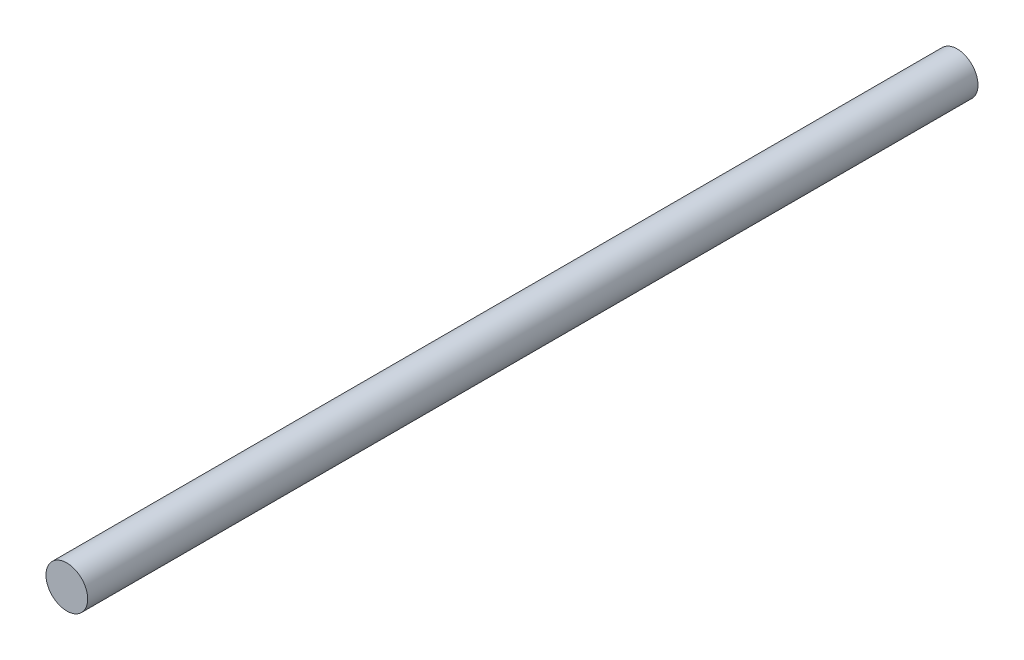
SolidWorks part; units mm, degrees
material "PE High Density"
ref_plane "Front Plane" through (0, 0, 0) normal (0, 0, 1) x (1, 0, 0)
ref_plane "Top Plane" through (0, 0, 0) normal (0, 1, 0) x (1, 0, 0)
ref_plane "Right Plane" through (0, 0, 0) normal (1, 0, 0) x (0, 0, -1)
sketch "Sketch1" plane through (0, 0, 0) normal (0, 0, 1) x (1, 0, 0)
  circle A0 centre (0, 0) radius 0.75
  dimension "D1" = 1.5
extrude "Boss-Extrude1" add sketch "Sketch1" along normal blind 32
